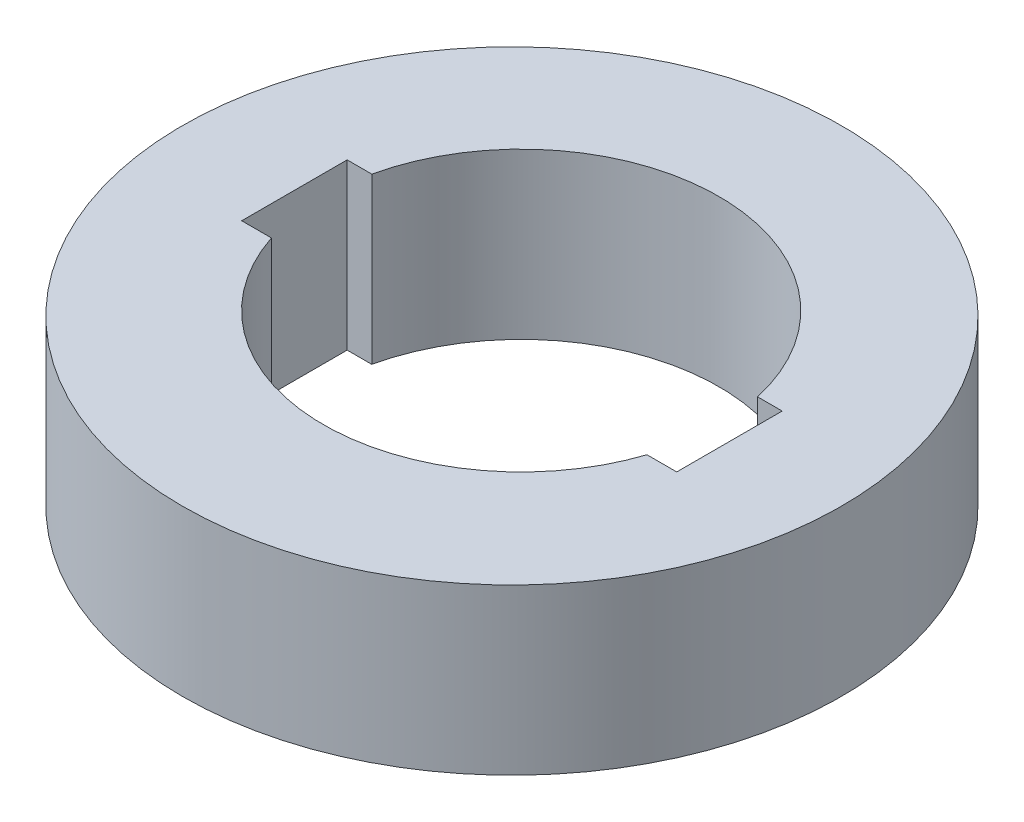
SolidWorks part; units mm, degrees
ref_plane "Front Plane" through (0, 0, 0) normal (0, 0, 1) x (1, 0, 0)
ref_plane "Top Plane" through (0, 0, 0) normal (0, 1, 0) x (1, 0, 0)
ref_plane "Right Plane" through (0, 0, 0) normal (1, 0, 0) x (0, 0, -1)
sketch "Sketch2" plane through (0, 0, 0) normal (0, 1, 0) x (1, 0, 0)
  line L1 (0, 50) -> (0, 72.2671) construction
  line L3 (33, 0) -> (33, 8)
  line L4 (33, 0) -> (33, -8)
  line L5 (33, -8) -> (28.4879, -8)
  line L6 (33, 8) -> (29.266, 8)
  line L8 (-33, -8) -> (-28.4879, -8)
  line L9 (-33, 0) -> (-33, -8)
  line L10 (-33, 0) -> (-33, 8)
  line L11 (-33, 8) -> (-29.266, 8)
  circle A0 centre (0, 0) radius 50
  arc A1 (29.266, 8) -> (-29.266, 8) centre (0, 1.4043) ccw
  arc A2 (-28.4879, -8) -> (28.4879, -8) centre (0, 1.4043) ccw
  dimension "D1" = 100
  dimension "D2" = 60
  dimension "D3" = 33
  dimension "D5" = 16
extrude "Boss-Extrude1" add sketch "Sketch2" against normal blind 25
